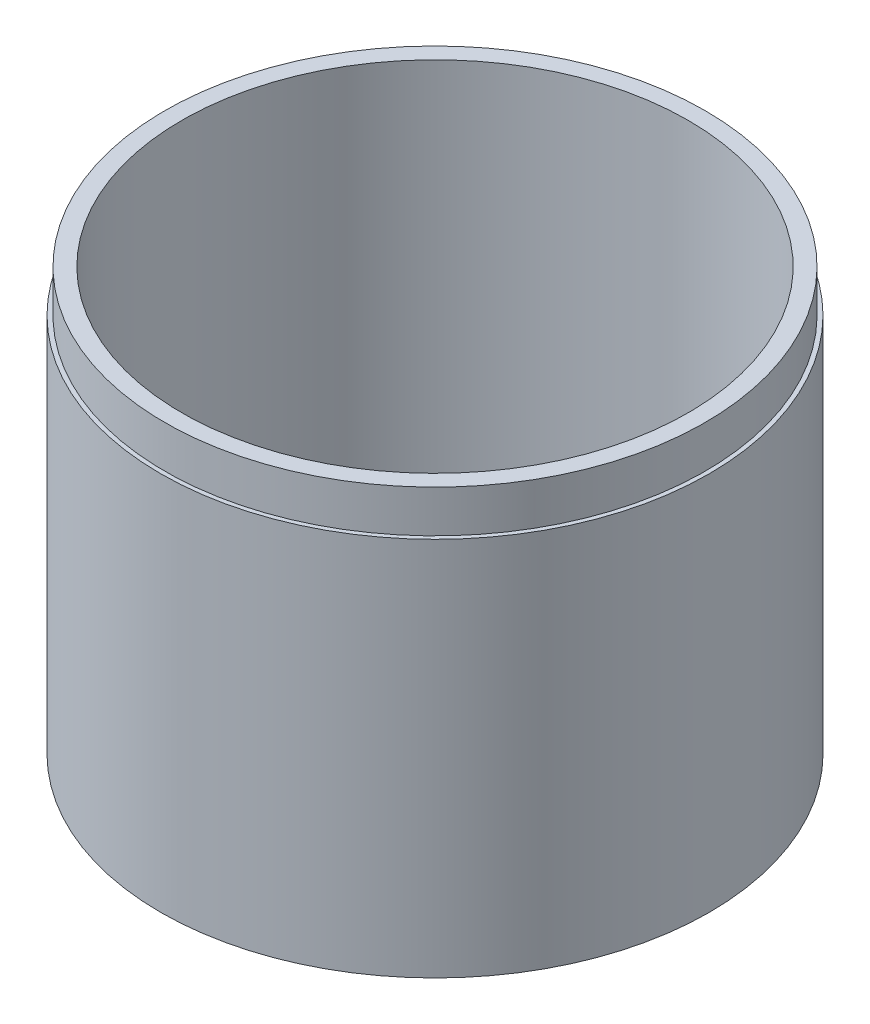
SolidWorks part; units mm, degrees
material "HYPALON"
ref_plane "Front Plane" through (0, 0, 0) normal (0, 0, 1) x (1, 0, 0)
ref_plane "Top Plane" through (0, 0, 0) normal (0, 1, 0) x (1, 0, 0)
ref_plane "Right Plane" through (0, 0, 0) normal (1, 0, 0) x (0, 0, -1)
sketch "Szkic1" plane through (0, 0, 0) normal (0, 0, 1) x (1, 0, 0)
  line L0 (0, 0) -> (-65, 0)
  line L1 (-65, 0) -> (-65, 10)
  line L2 (-63, 10) -> (-60, 10)
  line L3 (-60, 10) -> (-60, 100)
  line L4 (-63, 10) -> (-63, 0)
  line L5 (-60, 100) -> (-64, 100)
  line L7 (-65, 10) -> (-65, 90)
  line L8 (-65, 90) -> (-64, 90)
  line L9 (-64, 90) -> (-64, 100)
  line L13 (0, 0) -> (0, 22.4148)
  point P5 (0, 0)
  dimension "D1" = 65
  dimension "D2" = 10
  dimension "D3" = 5
  dimension "D4" = 100
  dimension "D7" = 1
  dimension "D8" = 10
  dimension "D13" = 3
revolve "Obrót1" add sketch "Szkic1" angle 360 about L13
